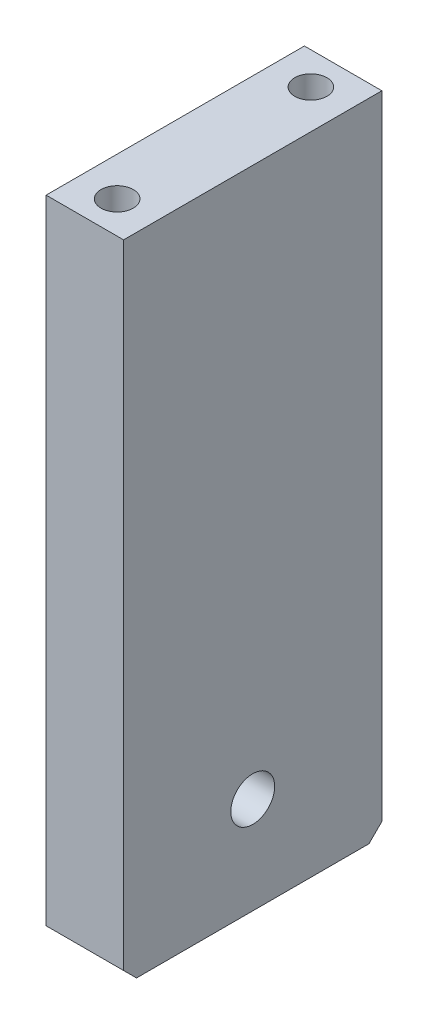
SolidWorks part; units mm, degrees
material "6061"
ref_plane "前视" through (0, 0, 0) normal (0, 0, 1) x (1, 0, 0)
ref_plane "上视" through (0, 0, 0) normal (0, 1, 0) x (1, 0, 0)
ref_plane "右视" through (0, 0, 0) normal (1, 0, 0) x (0, 0, -1)
sketch "草图1" plane through (0, 0, 0) normal (0, 1, 0) x (1, 0, 0)
  line L1 (-6, -20) -> (6, -20)
  line L2 (-6, -20) -> (-6, 20)
  line L3 (-6, 20) -> (6, 20)
  line L4 (6, -20) -> (6, 20)
  line L5 (-6, -20) -> (6, 20) construction
  line L6 (-6, 20) -> (6, -20) construction
  point P0 (0, 0)
  dimension "D1" = 12
  dimension "D2" = 40
extrude "凸台-拉伸1" add sketch "草图1" along normal blind 100
hole_wizard "M6 螺纹孔1" positions "草图3" profile "草图2" tap size "M6" standard "Gb"
sketch "草图3" plane through (0, 100, 0) normal (0, 1, 0) x (1, 0, 0)
  line L0 (0, 20) -> (0, 0) construction
  line L1 (6, 20) -> (-6, 20) construction
  line L2 (0, 0) -> (6, 0) construction
  line L3 (6, -20) -> (6, 20) construction
  point P0 (0, 15)
  point P15 (0, -15)
  dimension "D1" = 30
sketch "草图2" plane through (0, 100, -15) normal (1, 0, 0) x (0, 0, 1)
  line L0 (0, 0) -> (0, 16.5022)
  line L1 (0, 16.5022) -> (2.5, 15)
  line L2 (2.5, 15) -> (2.5, 0)
  line L5 (2.5, 0) -> (0, 0)
  line L10 (0, 16.5022) -> (-2.5, 15) construction
  line L11 (0, -6.35) -> (0, 107.95) construction
  dimension "螺纹孔钻头直径" = 5
  dimension "螺纹孔钻头深度" = 15
  dimension "导头角度" = 118
cosmetic thread "孔螺蚊线1"
cosmetic thread "孔螺蚊线2"
hole_wizard "M8 螺纹孔1" positions "草图5" profile "草图4" tap size "M8" standard "Gb" end condition through all
sketch "草图5" plane through (6, 0, 0) normal (1, 0, 0) x (0, 0, -1)
  line L0 (0, 100) -> (0, 15.1437) construction
  line L1 (-20, 100) -> (20, 100) construction
  point P0 (0, 15)
  dimension "D1" = 85
sketch "草图4" plane through (6, 15, 0) normal (0, 1, 0) x (0, 0, -1)
  line L0 (0, 0) -> (0, 12)
  line L1 (0, 12) -> (3.4, 12)
  line L2 (3.4, 12) -> (3.4, 0)
  line L5 (3.4, 0) -> (0, 0)
  line L11 (0, -6.35) -> (0, 107.95) construction
  dimension "通孔螺纹孔钻头直径" = 6.8
  dimension "通孔螺纹孔钻头深度" = 12
cosmetic thread "孔螺蚊线3"
chamfer "倒角1" distance 2 angle 45 2 edges at (0, 0, -20) (0, 0, 20)
